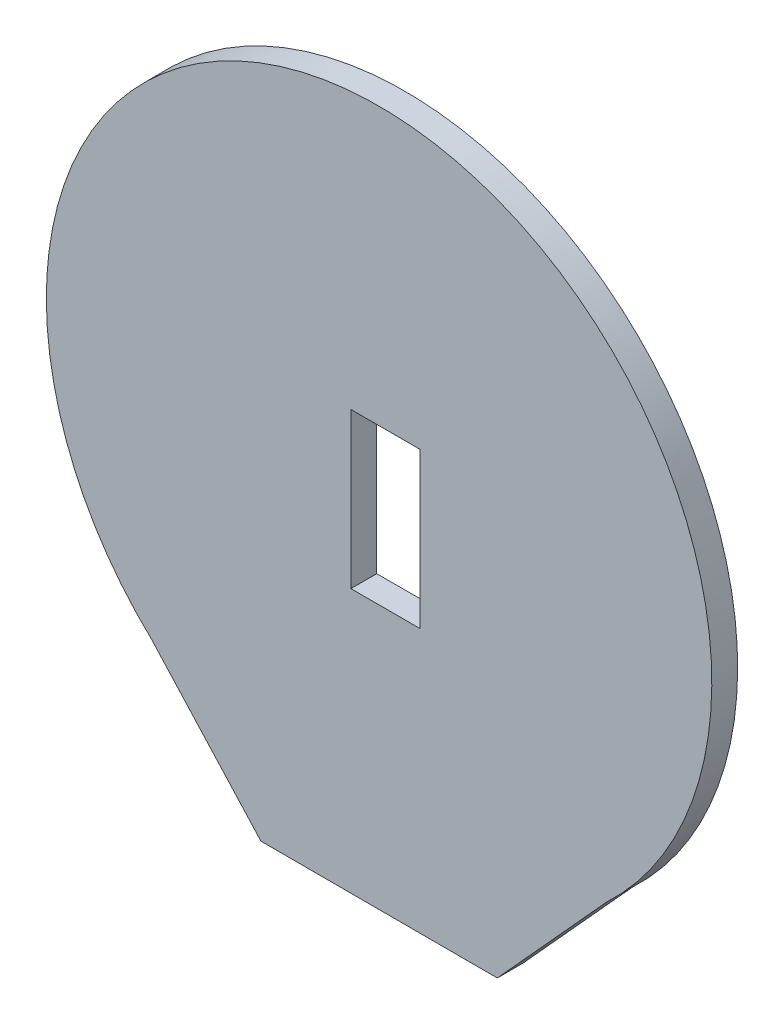
SolidWorks part; units mm, degrees
ref_plane "Front Plane" through (0, 0, 0) normal (0, 0, 1) x (1, 0, 0)
ref_plane "Top Plane" through (0, 0, 0) normal (0, 1, 0) x (1, 0, 0)
ref_plane "Right Plane" through (0, 0, 0) normal (1, 0, 0) x (0, 0, -1)
sketch "Sketch1" plane through (0, 0, 0) normal (0, 0, 1) x (1, 0, 0)
  line L20 (-17.3105, -21.8239) -> (-3.5977, -21.8436)
  line L21 (-3.5977, -21.8436) -> (2.7579, -14.8425)
  line L22 (-17.3105, -21.8239) -> (-23.6681, -14.8425)
  arc A4 (2.7579, -14.8425) -> (-23.6681, -14.8425) centre (-10.4551, -0.7746) ccw
  dimension "D1" = 19.3
extrude "Boss-Extrude1" add sketch "Sketch1" along normal blind 1.5 contours A4 L22 L20 L21
sketch "Sketch2" plane through (0, 0, 1.5) normal (0, 0, 1) x (1, 0, 0)
  line L3 (-12.0905, 2.4705) -> (-8.0905, 2.4705)
  line L4 (-12.0905, 2.4705) -> (-12.0905, -6.5295)
  line L5 (-12.0905, -6.5295) -> (-8.0905, -6.5295)
  line L6 (-8.0905, 2.4705) -> (-8.0905, -6.5295)
  line L7 (-12.0905, 2.4705) -> (-8.0905, -6.5295) construction
  line L8 (-12.0905, -6.5295) -> (-8.0905, 2.4705) construction
  point P8 (-10.0905, -2.0295)
  dimension "D1" = 9
  dimension "D2" = 4
extrude "Cut-Extrude1" cut sketch "Sketch2" against normal up to next
